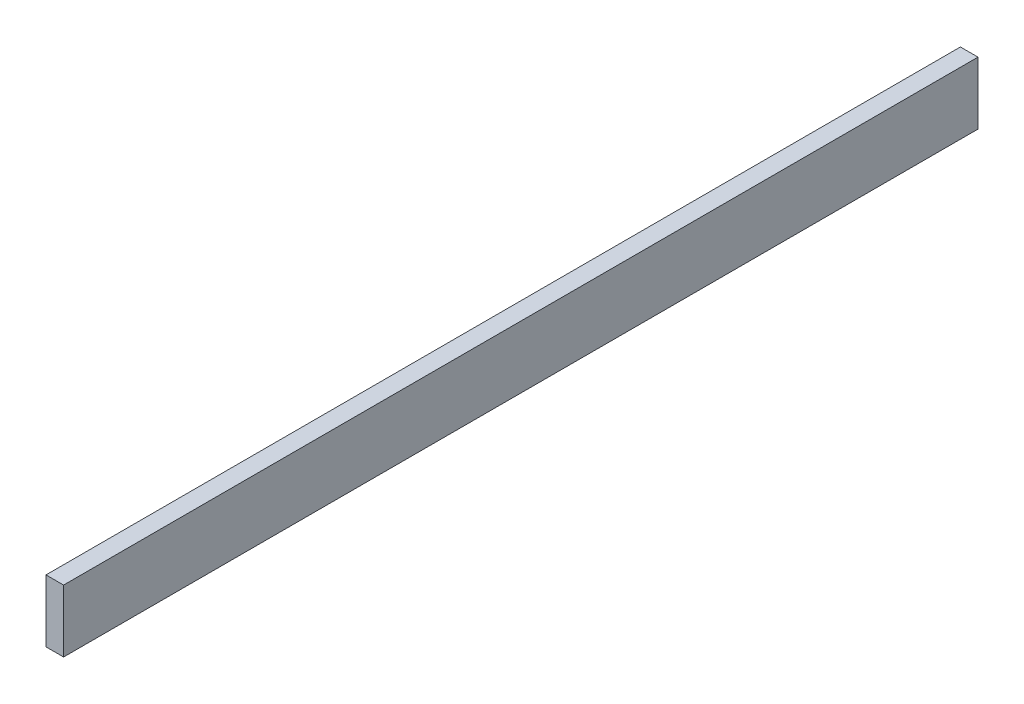
SolidWorks part; units mm, degrees
ref_plane "Front Plane" through (0, 0, 0) normal (0, 0, 1) x (1, 0, 0)
ref_plane "Top Plane" through (0, 0, 0) normal (0, 1, 0) x (1, 0, 0)
ref_plane "Right Plane" through (0, 0, 0) normal (1, 0, 0) x (0, 0, -1)
other "Configuration Table"
sketch "Sketch1" plane through (0, 0, 0) normal (0, 0, 1) x (1, 0, 0)
  line L1 (0, 18) -> (12.7, 18)
  line L2 (0, 18) -> (0, 63)
  line L3 (0, 63) -> (12.7, 63)
  line L4 (12.7, 18) -> (12.7, 63)
extrude "CEK_taze_ray_ic_profil_sol_1" add sketch "Sketch1" against normal blind 660 separate body
